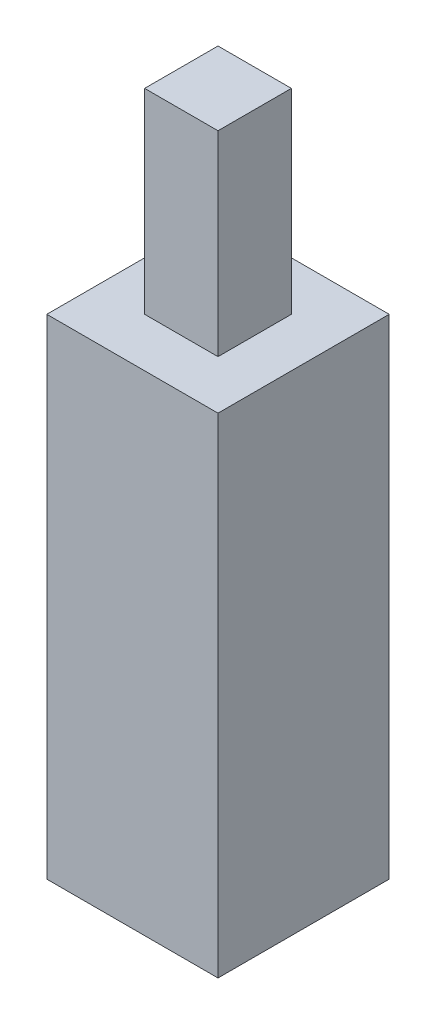
SolidWorks part; units mm, degrees
ref_plane "Front Plane" through (0, 0, 0) normal (0, 0, 1) x (1, 0, 0)
ref_plane "Top Plane" through (0, 0, 0) normal (0, 1, 0) x (1, 0, 0)
ref_plane "Right Plane" through (0, 0, 0) normal (1, 0, 0) x (0, 0, -1)
sketch "Sketch1" plane through (0, 0, 0) normal (0, 1, 0) x (1, 0, 0)
  line L1 (0, 0) -> (7, 0)
  line L2 (0, 0) -> (0, 7)
  line L3 (0, 7) -> (7, 7)
  line L4 (7, 0) -> (7, 7)
  dimension "D1" = 7
  dimension "D2" = 7
extrude "Boss-Extrude1" add sketch "Sketch1" along normal blind 20
sketch "Sketch2" plane through (0, 20, 0) normal (0, 1, 0) x (1, 0, 0)
  line L0 (7, 7) -> (0, 7) construction
  line L1 (2, 2) -> (5, 2)
  line L2 (2, 2) -> (2, 5)
  line L3 (2, 5) -> (5, 5)
  line L4 (5, 2) -> (5, 5)
  line L5 (0, 7) -> (0, 0) construction
  dimension "D1" = 3
  dimension "D2" = 3
  dimension "D3" = 2
  dimension "D4" = 2
extrude "Boss-Extrude2" add sketch "Sketch2" along normal blind 8
